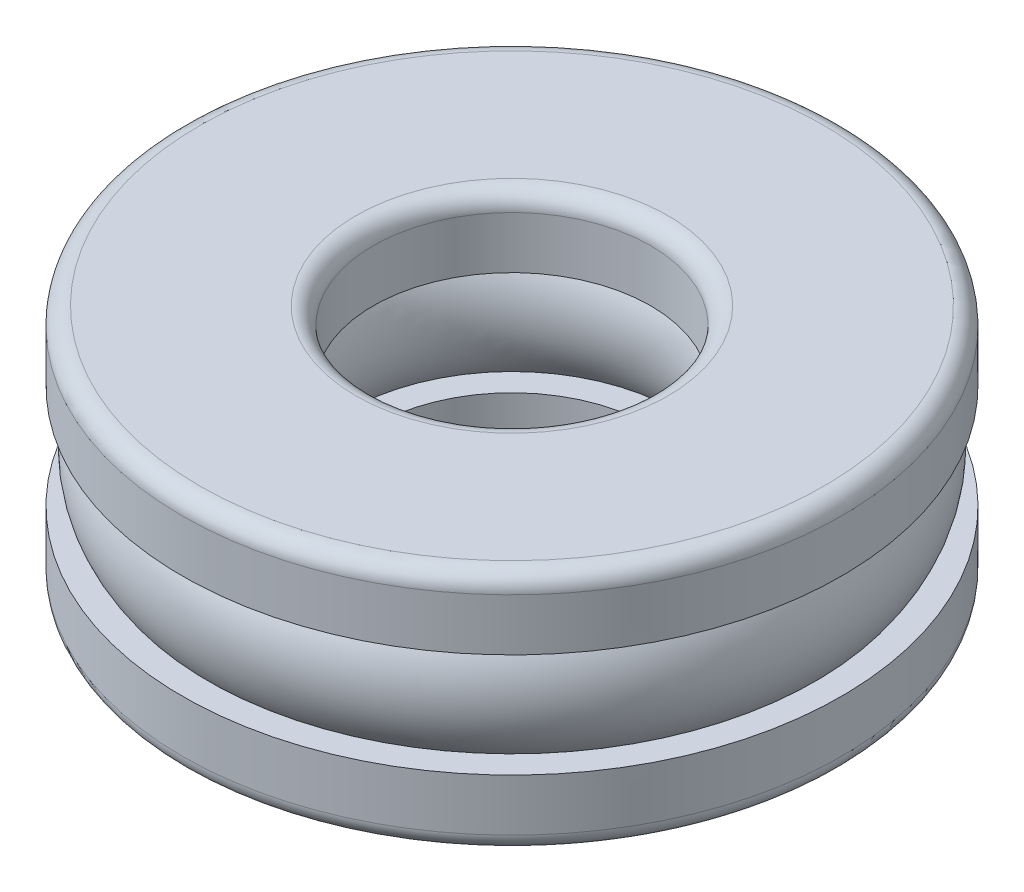
SolidWorks part; units mm, degrees
material "AISI 1020"
ref_plane "Plano frontal" through (0, 0, 0) normal (0, 0, 1) x (1, 0, 0)
ref_plane "Plano superior" through (0, 0, 0) normal (0, 1, 0) x (1, 0, 0)
ref_plane "Plano direito" through (0, 0, 0) normal (1, 0, 0) x (0, 0, -1)
sketch "Esboço1" plane through (0, 0, 0) normal (0, 0, 1) x (1, 0, 0)
  line L0 (0, 0) -> (0, 20.8212) construction
  line L1 (0, 0) -> (-6.75, 0) construction
  line L2 (-6.75, 0) -> (-6.75, 2.5) construction
  line L3 (-9.5, 3.5) -> (-4, 3.5)
  line L4 (-9.5, 3.5) -> (-9.5, 1.5)
  line L5 (-9.5, 1.5) -> (-4, 1.5)
  line L6 (-4, 3.5) -> (-4, 1.5)
  line L7 (-9.5, 3.5) -> (-4, 1.5) construction
  line L8 (-9.5, 1.5) -> (-4, 3.5) construction
  line L9 (-9.5, -1.5) -> (-4, -3.5) construction
  line L10 (-9.5, -3.5) -> (-4, -1.5) construction
  line L11 (-4, -3.5) -> (-4, -1.5)
  line L12 (-9.5, -1.5) -> (-4, -1.5)
  line L13 (-9.5, -3.5) -> (-9.5, -1.5)
  line L14 (-9.5, -3.5) -> (-4, -3.5)
  circle A0 centre (-6.75, 0) radius 2.5
  point P5 (-6.75, 2.5)
  point P15 (-6.75, -2.5)
  dimension "D1" = 19
  dimension "D2" = 8
  dimension "D3" = 7
  dimension "D4" = 3
revolve "Revolução1" add sketch "Esboço1" angle 360 about L0
fillet "Filete1" radius 0.5 4 edges at (0, -3.5, -9.5) (0, -3.5, -4) (0, 3.5, -9.5) (0, 3.5, -4)
